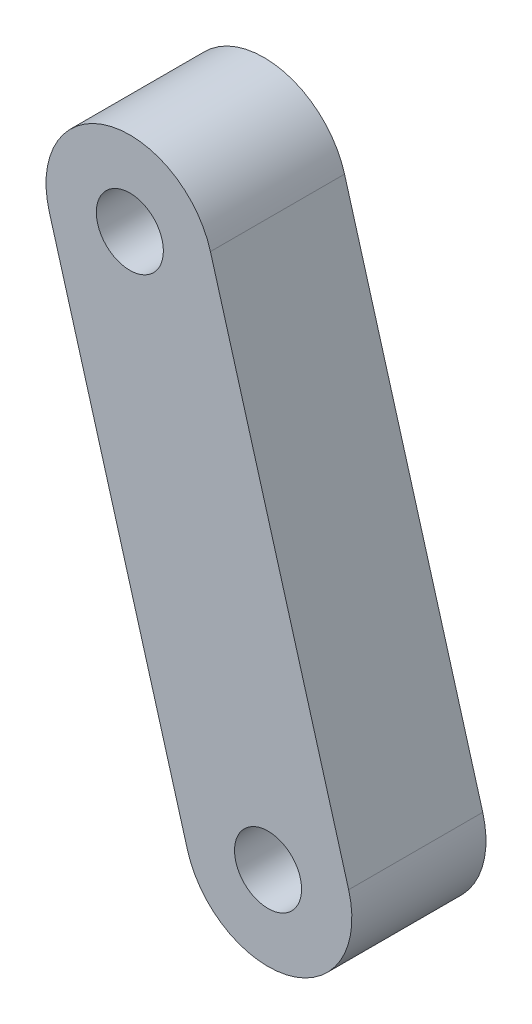
SolidWorks part; units mm, degrees
material "1060 合金"
ref_plane "前视基准面" through (0, 0, 0) normal (0, 0, 1) x (1, 0, 0)
ref_plane "上视基准面" through (0, 0, 0) normal (0, 1, 0) x (1, 0, 0)
ref_plane "右视基准面" through (0, 0, 0) normal (1, 0, 0) x (0, 0, -1)
sketch "连杆几何关系" plane through (0, 0, 0) normal (0, 0, 1) x (1, 0, 0)
  line L0 (0, 0) -> (20, 0)
  line L1 (20, 0) -> (77.07, 18.5208)
  line L2 (77.07, 18.5208) -> (143, -5)
  line L3 (7.3409, -5) -> (163.0583, -5)
  line L4 (0, 0) -> (-15, 0)
  line L5 (-15, 0) -> (-15, 80)
  line L6 (-15, 80) -> (21.7328, 64.1664)
  line L7 (77.07, 18.5208) -> (29.9771, 35.3214)
  line L8 (29.9771, 35.3214) -> (21.7328, 64.1664)
  line L9 (20, 0) -> (72.489, 29.0672)
  line L10 (72.489, 29.0672) -> (133.6399, -5)
  line L11 (28.8099, 53.4009) -> (24.8764, 83.1419)
  line L12 (24.8764, 83.1419) -> (-15, 80)
  line L13 (72.489, 29.0672) -> (28.8099, 53.4009)
  dimension "D1" = 20
  dimension "D2" = 15
  dimension "D3" = 60
  dimension "D4" = 70
  dimension "D5" = 5
  dimension "D6" = 80
  dimension "D7" = 40
  dimension "D8" = 50
  dimension "D9" = 143
  dimension "D10" = 30
sketch "草图1" plane through (0, 0, 0) normal (0, 0, 1) x (1, 0, 0)
  line L0 (21.7328, 64.1664) -> (29.9771, 35.3214) construction
  line L1 (26.5403, 65.5404) -> (34.7846, 36.6954)
  line L2 (16.9253, 62.7923) -> (25.1696, 33.9473)
  arc A0 (26.5403, 65.5404) -> (16.9253, 62.7923) centre (21.7328, 64.1664) ccw
  arc A1 (25.1696, 33.9473) -> (34.7846, 36.6954) centre (29.9771, 35.3214) ccw
  circle A2 centre (21.7328, 64.1664) radius 2
  circle A3 centre (29.9771, 35.3214) radius 2
  point P4 (25.8549, 49.7439)
  dimension "D1" = 5
  dimension "D2" = 4
extrude "凸台-拉伸1" add sketch "草图1" along normal mid plane 8
